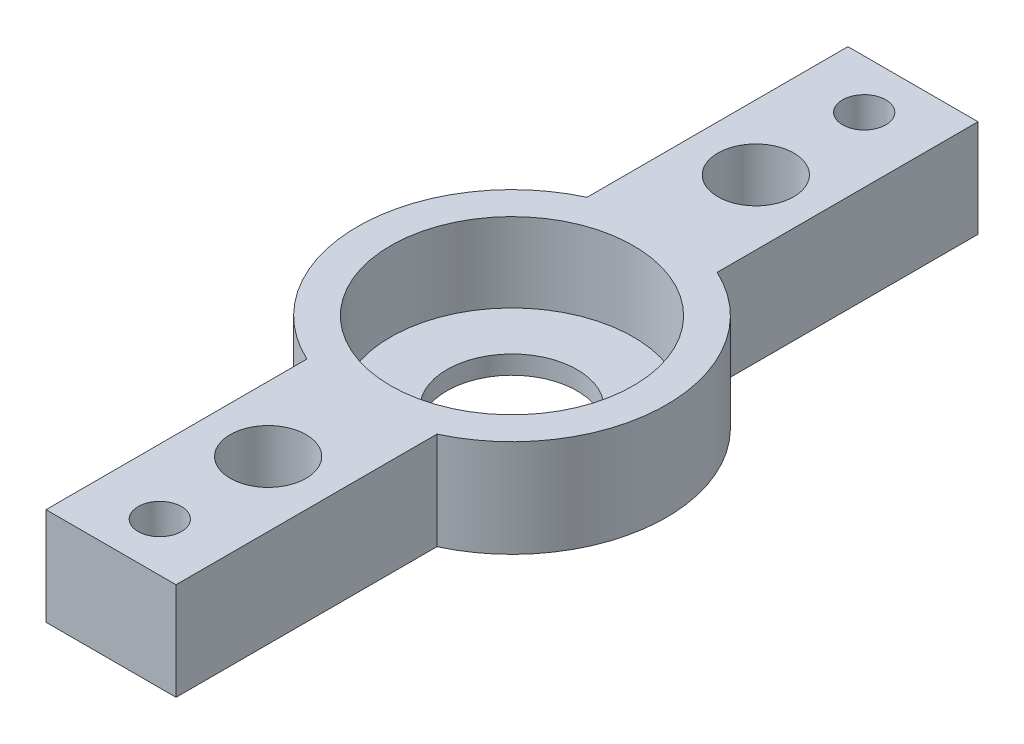
SolidWorks part; units mm, degrees
ref_plane "Front Plane" through (0, 0, 0) normal (0, 0, 1) x (1, 0, 0)
ref_plane "Top Plane" through (0, 0, 0) normal (0, 1, 0) x (1, 0, 0)
ref_plane "Right Plane" through (0, 0, 0) normal (1, 0, 0) x (0, 0, -1)
sketch "Sketch1" plane through (0, 0, 0) normal (0, 1, 0) x (1, 0, 0)
  line L0 (0, 0) -> (0, 37) construction
  line L1 (-6, 37) -> (6, 37)
  line L2 (6, 37) -> (6, 12.9253)
  line L3 (-6, 37) -> (-6, 12.9253)
  line L4 (0, 0) -> (6.7962, 0) construction
  line L5 (6, -37) -> (6, -12.9253)
  line L6 (-6, -37) -> (6, -37)
  line L7 (-6, -37) -> (-6, -12.9253)
  arc A0 (-6, 12.9253) -> (-6, -12.9253) centre (0, 0) ccw
  circle A1 centre (0, 22.5) radius 3.5
  circle A2 centre (0, 32.5) radius 2
  circle A3 centre (0, -22.5) radius 3.5
  circle A4 centre (0, -32.5) radius 2
  arc A5 (6, -12.9253) -> (6, 12.9253) centre (0, 0) ccw
  dimension "D1" = 28.5
  dimension "D2" = 7
  dimension "D4" = 4
  dimension "D3" = 22.5
  dimension "D5" = 10
  dimension "D6" = 37
  dimension "D7" = 6
extrude "Boss-Extrude1" add sketch "Sketch1" along normal blind 9
ref_plane "Plane1" through (0, 9, 0) normal (0, 1, 0) x (1, 0, 0)
sketch "Sketch2" plane through (0, 9, 0) normal (0, 1, 0) x (1, 0, 0)
  circle A0 centre (0, 0) radius 11.2
  dimension "D1" = 22.4
extrude "Cut-Extrude1" cut sketch "Sketch2" against normal blind 7.3
ref_plane "Plane2" through (0, 1.7, 0) normal (0, 1, 0) x (1, 0, 0)
sketch "Sketch3" plane through (0, 1.7, 0) normal (0, 1, 0) x (1, 0, 0)
  circle A0 centre (0, 0) radius 6
  dimension "D1" = 12
extrude "Cut-Extrude2" cut sketch "Sketch3" against normal up to next
